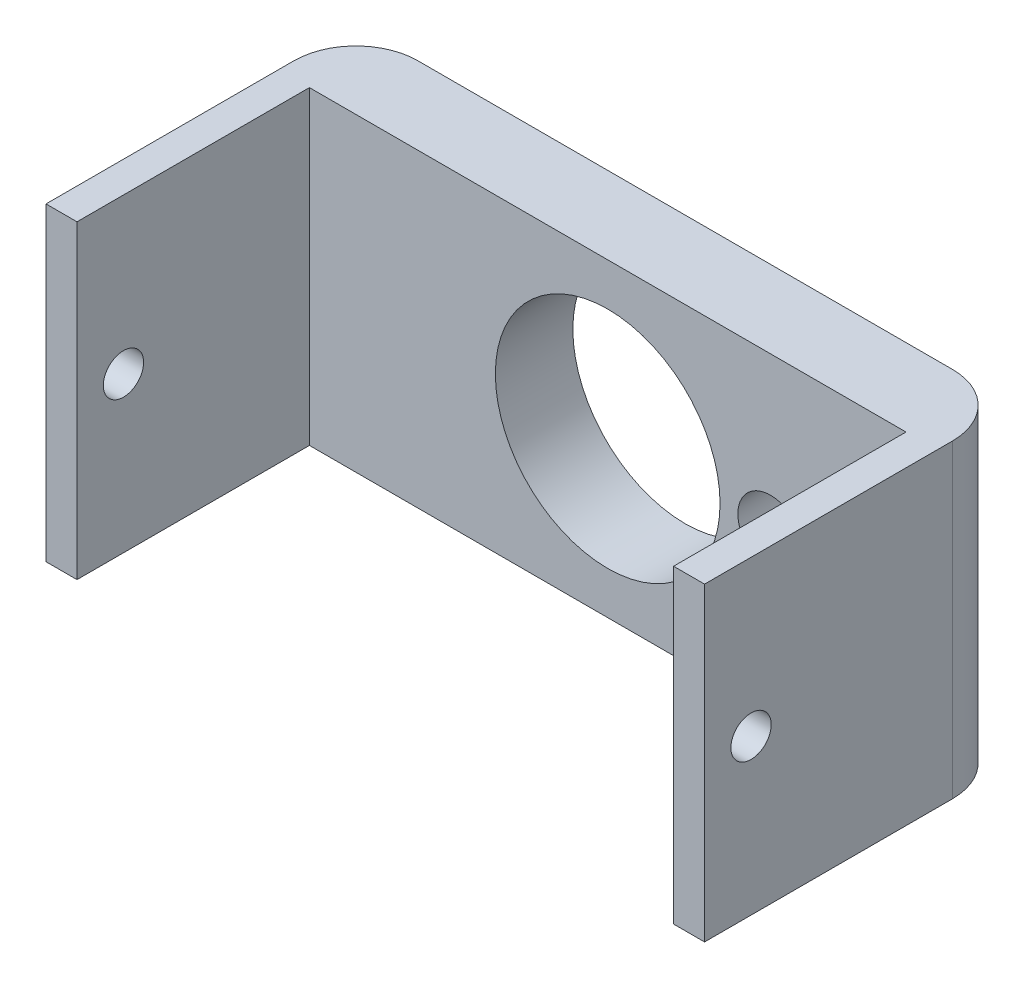
SolidWorks part; units mm, degrees
ref_plane "前视基准面" through (0, 0, 0) normal (0, 0, 1) x (1, 0, 0)
ref_plane "上视基准面" through (0, 0, 0) normal (0, 1, 0) x (1, 0, 0)
ref_plane "右视基准面" through (0, 0, 0) normal (1, 0, 0) x (0, 0, -1)
other "Configuration Table"
sketch "草图1" plane through (0, 0, 0) normal (0, 0, 1) x (1, 0, 0)
  line L1 (-21.25, -10) -> (21.25, -10)
  line L2 (-21.25, -10) -> (-21.25, 10)
  line L3 (-21.25, 10) -> (21.25, 10)
  line L4 (21.25, -10) -> (21.25, 10)
  line L5 (-21.25, -10) -> (21.25, 10) construction
  line L6 (-21.25, 10) -> (21.25, -10) construction
  point P0 (0, 0)
  dimension "D1" = 42.5
  dimension "D2" = 20
extrude "凸台-拉伸1" add sketch "草图1" along normal blind 20
sketch "草图2" plane through (0, 0, 20) normal (0, 0, 1) x (1, 0, 0)
  line L0 (21.25, 10) -> (-21.25, 10) construction
  line L1 (-19.25, 10) -> (19.25, 10)
  line L2 (-19.25, 10) -> (-19.25, -10)
  line L3 (-19.25, -10) -> (19.25, -10)
  line L4 (19.25, 10) -> (19.25, -10)
  line L5 (-21.25, -10) -> (21.25, -10) construction
  line L6 (-21.25, 10) -> (-21.25, -10) construction
  dimension "D1" = 38.5
  dimension "D2" = 2
extrude "切除-拉伸1" cut sketch "草图2" against normal offset from surface (15 mm away) 5 up to face at (0, 0, 0)
sketch "草图3" plane through (0, 0, 0) normal (0, 0, -1) x (-1, 0, 0)
  circle A0 centre (0, 0) radius 7.25
  dimension "D1" = 14.5
extrude "切除-拉伸2" cut sketch "草图3" against normal up to surface (5 mm away) up to face at (0, 0, 5)
sketch "草图4" plane through (21.25, 0, 0) normal (1, 0, 0) x (0, 0, -1)
  line L0 (-20, -10) -> (-20, 10) construction
  line L1 (-23.1488, 0) -> (2.6596, 0) construction
  circle A0 centre (-17, 0) radius 1.3
  dimension "D2" = 2.6
  dimension "D1" = 3
extrude "切除-拉伸3" cut sketch "草图4" against normal up to surface (42.5 mm away) up to face at (-21.25, 0, 10)
sketch "草图5" plane through (0, 0, 0) normal (0, 0, -1) x (-1, 0, 0)
  line L0 (-16.5125, 0) -> (12.4896, 0) construction
  circle A0 centre (-10.5, 0) radius 2.1
  dimension "D1" = 4.2
  dimension "D2" = 10.5
extrude "切除-拉伸4" cut sketch "草图5" against normal up to surface (5 mm away) up to face at (-7.25, 0, 5)
fillet "圆角1" radius 4 2 edges at (-21.25, 0, 0) (21.25, 0, 0)
